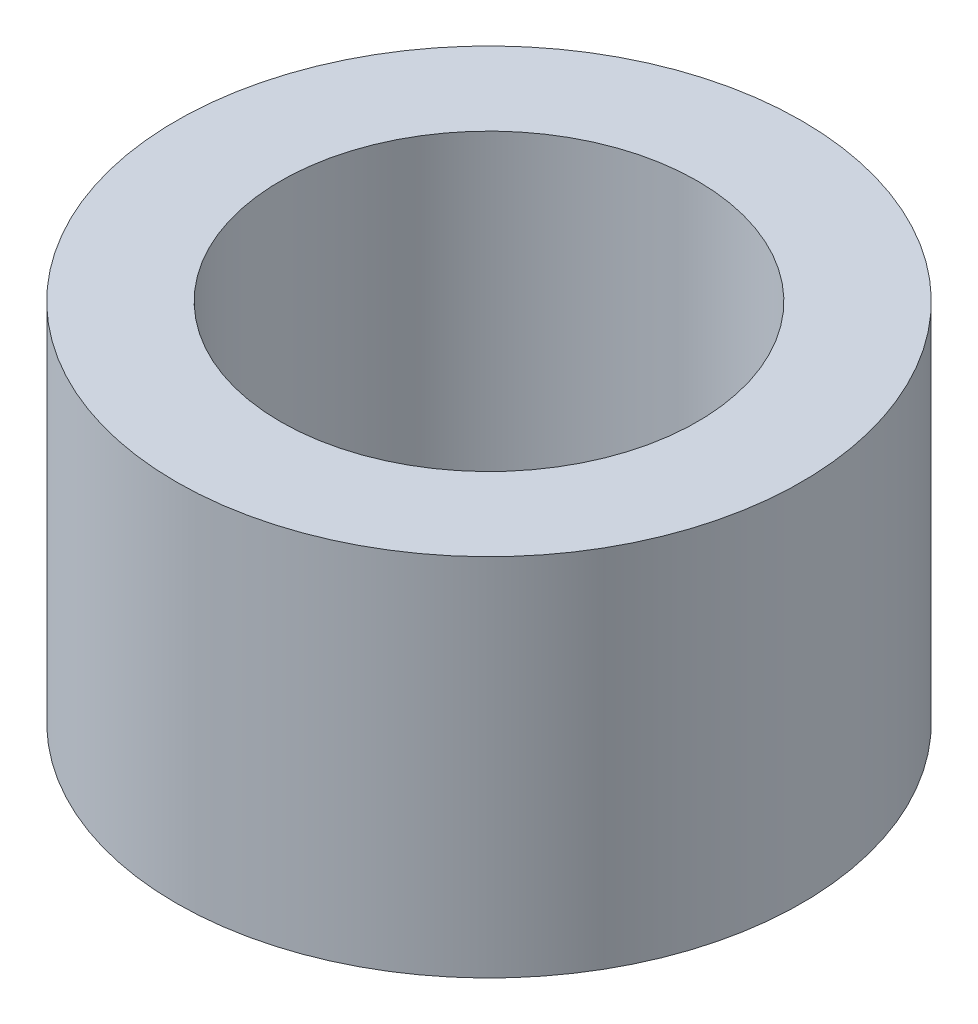
SolidWorks part; units mm, degrees
ref_plane "Спереди" through (0, 0, 0) normal (0, 0, 1) x (1, 0, 0)
ref_plane "Сверху" through (0, 0, 0) normal (0, 1, 0) x (1, 0, 0)
ref_plane "Справа" through (0, 0, 0) normal (1, 0, 0) x (0, 0, -1)
sketch "Эскиз1" plane through (0, 0, 0) normal (0, 1, 0) x (1, 0, 0)
  circle A0 centre (0, 0) radius 2
  circle A1 centre (0, 0) radius 3
  dimension "D1" = 4
  dimension "D2" = 6
extrude "Бобышка-Вытянуть1" add sketch "Эскиз1" along normal blind 3.5
